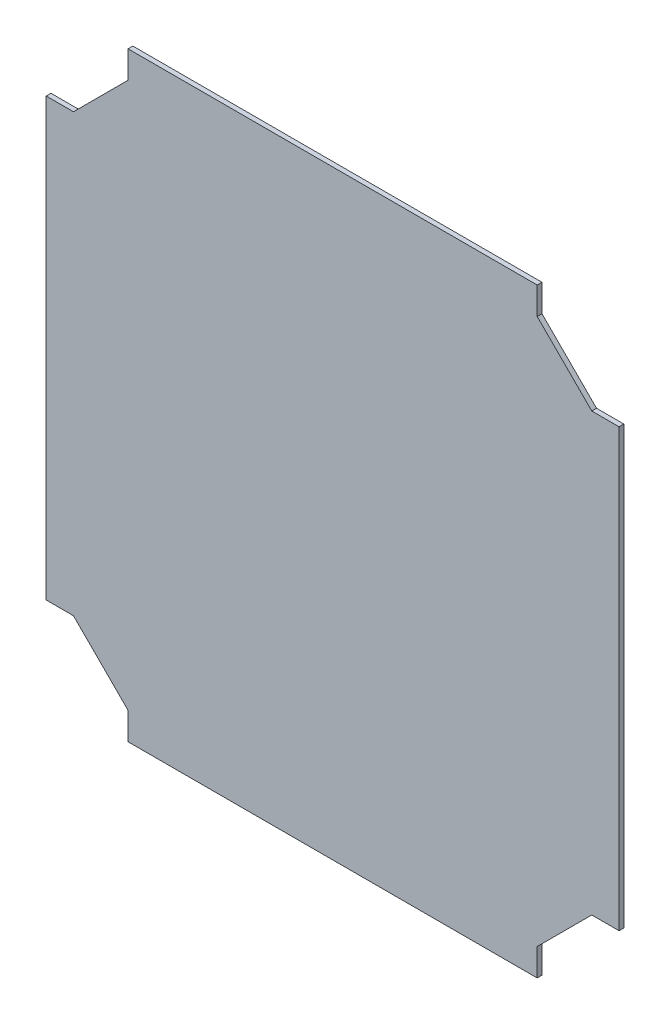
SolidWorks part; units mm, degrees
ref_plane "Front Plane" through (0, 0, 0) normal (0, 0, 1) x (1, 0, 0)
ref_plane "Top Plane" through (0, 0, 0) normal (0, 1, 0) x (1, 0, 0)
ref_plane "Right Plane" through (0, 0, 0) normal (1, 0, 0) x (0, 0, -1)
sketch "Sketch2" plane through (0, 0, 0) normal (0, 0, 1) x (1, 0, 0)
  line L0 (-74.4468, 440) -> (225.5532, 440)
  line L5 (225.5532, 440) -> (225.5532, 420)
  line L6 (225.5532, 420) -> (265.5532, 380)
  line L7 (265.5532, 380) -> (285.5532, 380)
  line L8 (285.5532, 380) -> (285.5532, 60)
  line L9 (285.5532, 60) -> (265.5532, 60)
  line L10 (265.5532, 60) -> (225.5532, 20)
  line L11 (225.5532, 20) -> (225.5532, 0)
  line L13 (-74.4468, 0) -> (-74.4468, 20)
  line L14 (-74.4468, 20) -> (-114.4468, 60)
  line L15 (-114.4468, 60) -> (-134.4468, 60)
  line L16 (-134.4468, 60) -> (-134.4468, 380)
  line L17 (-134.4468, 380) -> (-114.4468, 380)
  line L18 (-114.4468, 380) -> (-74.4468, 420)
  line L19 (-74.4468, 420) -> (-74.4468, 440)
  line L20 (-74.4468, 0) -> (0, 0)
  line L21 (0, 0) -> (225.5532, 0)
  point P17 (-124.4468, 60)
  dimension "D1" = 74.4468
  dimension "D2" = 440
  dimension "D3" = 440
  dimension "D4" = 300
  dimension "D5" = 134.4468
  dimension "D6" = 420
  dimension "D7" = 60
  dimension "D8" = 320
  dimension "D9" = 320
  dimension "D10" = 320
  dimension "D11" = 38.4997
  dimension "D12" = 20
  dimension "D13" = 494.9747
  dimension "D14" = 20
  dimension "D15" = 494.9747
  dimension "D16" = 20
  dimension "D17" = 20
  dimension "D18" = 74.4468
extrude "Boss-Extrude2" add sketch "Sketch2" along normal blind 3.5
